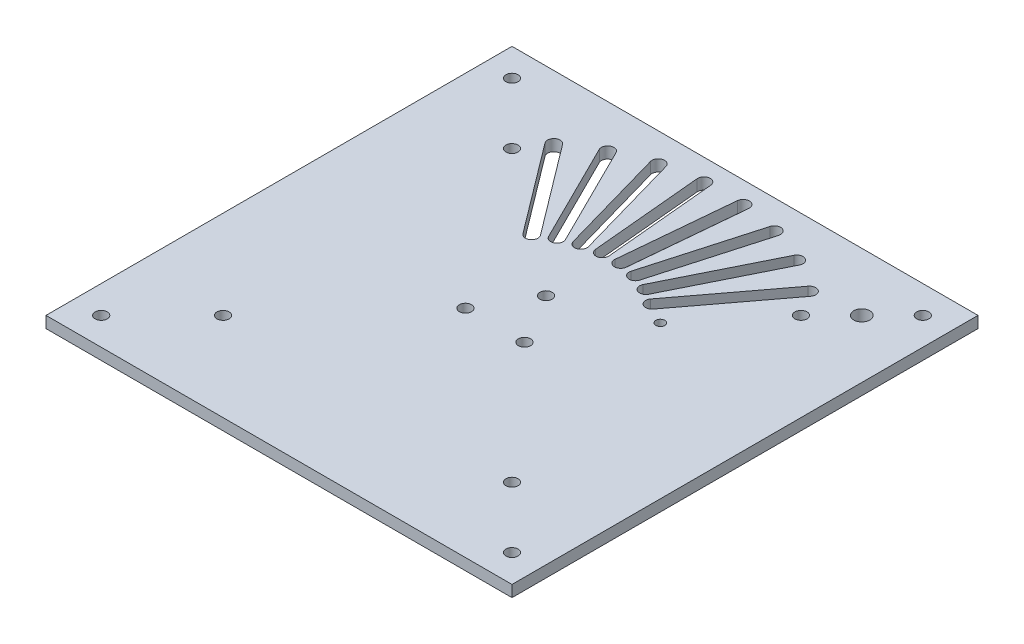
SolidWorks part; units mm, degrees
material "Acrylic (Medium-high impact)"
ref_plane "Front Plane" through (0, 0, 0) normal (0, 0, 1) x (1, 0, 0)
ref_plane "Top Plane" through (0, 0, 0) normal (0, 1, 0) x (1, 0, 0)
ref_plane "Right Plane" through (0, 0, 0) normal (1, 0, 0) x (0, 0, -1)
sketch "Sketch2" plane through (0, 0, 0) normal (0, 1, 0) x (1, 0, 0)
  line L1 (-65, -65) -> (65, -65)
  line L2 (-65, -65) -> (-65, 65)
  line L3 (-65, 65) -> (65, 65)
  line L4 (65, -65) -> (65, 65)
  line L5 (-65, -65) -> (65, 65) construction
  line L6 (-65, 65) -> (65, -65) construction
  point P0 (0, 0)
  dimension "D1" = 130
  dimension "D2" = 130
extrude "Boss-Extrude1" add sketch "Sketch2" along normal blind 3.2
sketch "Sketch4" plane through (0, 3.2, 0) normal (0, 1, 0) x (1, 0, 0)
  line L8 (57.3, -57.3) -> (57.3, 57.3)
  line L9 (57.3, 57.3) -> (-57.3, 57.3)
  line L10 (-57.3, 57.3) -> (-57.3, -57.3)
  line L11 (-57.3, -57.3) -> (57.3, -57.3)
  line L12 (57.3, -57.3) -> (57.3, 57.3) construction
  line L13 (57.3, 57.3) -> (-57.3, 57.3) construction
  line L14 (-57.3, 57.3) -> (-57.3, -57.3) construction
  line L15 (-57.3, -57.3) -> (57.3, -57.3) construction
  circle A0 centre (-57.3, 57.3) radius 1.7
  circle A1 centre (57.3, 57.3) radius 1.7
  circle A2 centre (57.3, -57.3) radius 1.7
  circle A3 centre (-57.3, -57.3) radius 1.7
  dimension "D2" = 3.4
  dimension "D1" = 7.7
extrude "Cut-Extrude1" cut sketch "Sketch4" against normal up to next
sketch "Sketch6" plane through (0, 3.2, 0) normal (0, 1, 0) x (1, 0, 0)
  line L6 (-40.3051, -40.3051) -> (40.3051, -40.3051) construction
  line L7 (-40.3051, -40.3051) -> (-40.3051, 40.3051) construction
  line L8 (-40.3051, 40.3051) -> (40.3051, 40.3051) construction
  line L9 (40.3051, -40.3051) -> (40.3051, 40.3051) construction
  line L10 (-40.3051, -40.3051) -> (40.3051, 40.3051) construction
  line L11 (-40.3051, 40.3051) -> (40.3051, -40.3051) construction
  circle A4 centre (-40.3051, 40.3051) radius 1.7
  circle A5 centre (40.3051, 40.3051) radius 1.7
  circle A6 centre (40.3051, -40.3051) radius 1.7
  circle A7 centre (-40.3051, -40.3051) radius 1.7
  point P0 (0, 0)
  dimension "D2" = 3.4
  dimension "D1" = 57
extrude "Cut-Extrude2" cut sketch "Sketch6" against normal up to next
sketch "Sketch8" plane through (0, 3.2, 0) normal (0, 1, 0) x (1, 0, 0)
  circle A4 centre (0, 9.5) radius 1.7
  circle A5 centre (8.2272, -4.75) radius 1.7
  circle A6 centre (-8.2272, -4.75) radius 1.7
  point P9 (0, 0)
  dimension "D1" = 9.5
  dimension "D3" = 3.4
  dimension "D2" = 3
extrude "Cut-Extrude3" cut sketch "Sketch8" against normal up to next
sketch "Sketch9" plane through (0, 3.2, 0) normal (0, 1, 0) x (1, 0, 0)
  line L0 (65, -65) -> (65, 65) construction
  line L1 (48.7904, 48.7904) -> (0, 0) construction
  line L2 (0, 0) -> (50000, 0) construction
  circle A0 centre (0, 0) radius 65 construction
  circle A1 centre (48.7904, 48.7904) radius 2.25
  dimension "D3" = 4
  dimension "D1" = 4.5
  dimension "D2" = 45
extrude "Primary wire hole" cut sketch "Sketch9" against normal up to next
sketch "Sketch10" plane through (0, 3.2, 0) normal (0, 1, 0) x (1, 0, 0)
  line L0 (0, 0) -> (22.5064, 18.8851) construction
  line L1 (0, 0) -> (50000, 0) construction
  circle A0 centre (0, 0) radius 24.13 construction
  circle A1 centre (22.5064, 18.8851) radius 1.25
  dimension "D1" = 48.26
  dimension "D3" = 2.5
  dimension "D2" = 40
  dimension "D4" = 4
extrude "Secondary wire hole" cut sketch "Sketch10" against normal up to next
sketch "Sketch11" plane through (0, 3.2, 0) normal (0, 1, 0) x (1, 0, 0)
  line L0 (-35.6575, 47.3192) -> (-16.7786, 22.266) construction
  line L1 (-34.2599, 48.3723) -> (-15.381, 23.3191)
  line L2 (-37.0552, 46.266) -> (-18.1762, 21.2128)
  line L3 (0, 0) -> (-16.7786, 22.266) construction
  line L4 (-27.9382, 52.2789) -> (-13.976, 24.1874)
  line L5 (-24.804, 53.8367) -> (-10.8418, 25.7452)
  line L6 (-26.3711, 53.0578) -> (-12.4089, 24.9663) construction
  line L7 (-17.8729, 56.5171) -> (-9.3013, 26.3409)
  line L8 (-14.5061, 57.4735) -> (-5.9345, 27.2972)
  line L9 (-16.1895, 56.9953) -> (-7.6179, 26.8191) construction
  line L10 (-7.2008, 58.8368) -> (-4.3109, 27.6002)
  line L11 (-3.7157, 59.1593) -> (-0.8258, 27.9227)
  line L12 (-5.4582, 58.9981) -> (-2.5684, 27.7614) construction
  line L13 (3.7157, 59.1593) -> (0.8258, 27.9227)
  line L14 (7.2008, 58.8368) -> (4.3109, 27.6002)
  line L15 (5.4582, 58.9981) -> (2.5684, 27.7614) construction
  line L18 (0, 0) -> (50000, 0) construction
  line L19 (14.5061, 57.4735) -> (5.9345, 27.2972)
  line L20 (17.8729, 56.5171) -> (9.3013, 26.3409)
  line L21 (16.1895, 56.9953) -> (7.6179, 26.8191) construction
  line L22 (24.804, 53.8367) -> (10.8418, 25.7452)
  line L23 (27.9382, 52.2789) -> (13.976, 24.1874)
  line L24 (26.3711, 53.0578) -> (12.4089, 24.9663) construction
  line L25 (34.2599, 48.3723) -> (15.381, 23.3191)
  line L26 (37.0552, 46.266) -> (18.1762, 21.2128)
  line L27 (35.6575, 47.3192) -> (16.7786, 22.266) construction
  line L28 (0, 0) -> (16.7786, 22.266) construction
  circle A0 centre (0, 0) radius 24.13 construction
  circle A1 centre (0, 0) radius 63 construction
  arc A2 (-34.2599, 48.3723) -> (-37.0552, 46.266) centre (-35.6575, 47.3192) ccw
  arc A3 (-18.1762, 21.2128) -> (-15.381, 23.3191) centre (-16.7786, 22.266) ccw
  arc A4 (-24.804, 53.8367) -> (-27.9382, 52.2789) centre (-26.3711, 53.0578) ccw
  arc A5 (-13.976, 24.1874) -> (-10.8418, 25.7452) centre (-12.4089, 24.9663) ccw
  arc A6 (-14.5061, 57.4735) -> (-17.8729, 56.5171) centre (-16.1895, 56.9953) ccw
  arc A7 (-9.3013, 26.3409) -> (-5.9345, 27.2972) centre (-7.6179, 26.8191) ccw
  arc A8 (-3.7157, 59.1593) -> (-7.2008, 58.8368) centre (-5.4582, 58.9981) ccw
  arc A9 (-4.3109, 27.6002) -> (-0.8258, 27.9227) centre (-2.5684, 27.7614) ccw
  arc A10 (7.2008, 58.8368) -> (3.7157, 59.1593) centre (5.4582, 58.9981) ccw
  arc A11 (0.8258, 27.9227) -> (4.3109, 27.6002) centre (2.5684, 27.7614) ccw
  arc A14 (17.8729, 56.5171) -> (14.5061, 57.4735) centre (16.1895, 56.9953) ccw
  arc A15 (5.9345, 27.2972) -> (9.3013, 26.3409) centre (7.6179, 26.8191) ccw
  arc A16 (27.9382, 52.2789) -> (24.804, 53.8367) centre (26.3711, 53.0578) ccw
  arc A17 (10.8418, 25.7452) -> (13.976, 24.1874) centre (12.4089, 24.9663) ccw
  arc A18 (37.0552, 46.266) -> (34.2599, 48.3723) centre (35.6575, 47.3192) ccw
  arc A19 (15.381, 23.3191) -> (18.1762, 21.2128) centre (16.7786, 22.266) ccw
  point P6 (-26.2181, 34.7926)
  point P17 (-19.39, 39.012)
  point P24 (-11.9037, 41.9072)
  point P31 (-4.0133, 43.3797)
  point P36 (0, 0)
  point P38 (4.0133, 43.3797)
  point P48 (11.9037, 41.9072)
  point P55 (19.39, 39.012)
  point P62 (26.2181, 34.7926)
  dimension "D1" = 48.26
  dimension "D2" = 126
  dimension "D3" = 2
  dimension "D4" = 2
  dimension "D5" = 3.5
  dimension "D7" = 53
  dimension "D8" = 53
  dimension "D6" = 8
extrude "Cut-Extrude6" cut sketch "Sketch11" against normal up to next
equation "\"D1@Sketch4\"=4.50+3.2"
equation "\"D1@Sketch10\"=1.9in"
equation "\"D1@Sketch11\"=1.9in"
equation "\"D2@Sketch11\"=130mm-2*2mm"
